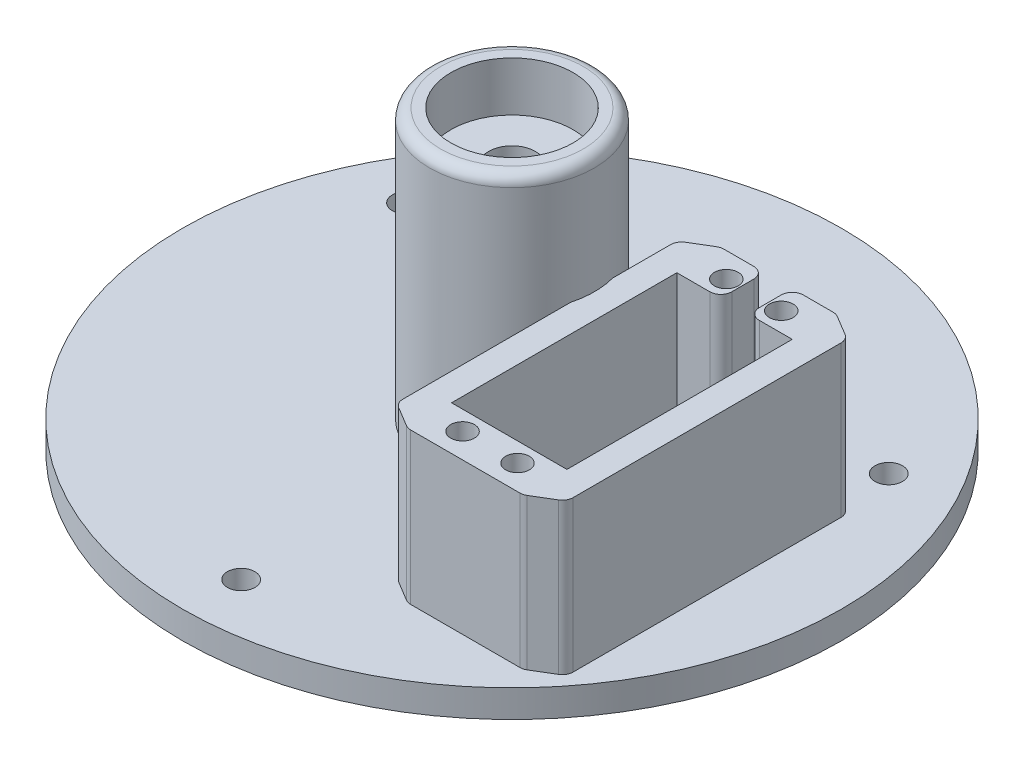
SolidWorks part; units mm, degrees
ref_plane "Front Plane" through (0, 0, 0) normal (0, 0, 1) x (1, 0, 0)
ref_plane "Top Plane" through (0, 0, 0) normal (0, 1, 0) x (1, 0, 0)
ref_plane "Right Plane" through (0, 0, 0) normal (1, 0, 0) x (0, 0, -1)
sketch "Sketch1" plane through (0, 0, 0) normal (0, 1, 0) x (1, 0, 0)
  circle A0 centre (0, 0) radius 60
  circle A1 centre (0, 0) radius 4.25
  dimension "D1" = 120
  dimension "D2" = 8.5
extrude "Boss-Extrude1" add sketch "Sketch1" along normal blind 5
sketch "Sketch2" plane through (0, 5, 0) normal (0, 1, 0) x (1, 0, 0)
  line L0 (20, 10) -> (30, 10) construction
  line L1 (40, 10) -> (40, -30) construction
  line L2 (40, -30) -> (20, -30) construction
  line L3 (20, -30) -> (20, 10) construction
  line L4 (30, 10) -> (30, 0) construction
  line L5 (19.5, 10.5) -> (27.5, 10.5)
  line L6 (40.5, 10.5) -> (40.5, -30.5)
  line L7 (40.5, -30.5) -> (19.5, -30.5)
  line L8 (19.5, -30.5) -> (19.5, 10.5)
  line L10 (45.5, 15.5) -> (45.5, -35.5)
  line L12 (14.5, -35.5) -> (14.5, 15.5)
  line L14 (19.5, 18.5) -> (27.5, 18.5)
  line L17 (19.5, -38.5) -> (40.5, -38.5)
  line L20 (14.5, 15.5) -> (45.5, 15.5) construction
  line L22 (45.5, -35.5) -> (14.5, -35.5) construction
  line L23 (27.5, 10.5) -> (27.5, 18.5)
  line L24 (32.5, 10.5) -> (32.5, 18.5)
  line L25 (32.5, 18.5) -> (40.5, 18.5)
  line L26 (32.5, 10.5) -> (40.5, 10.5)
  line L27 (19.5, 10.5) -> (40.5, 10.5) construction
  line L28 (20, 10) -> (40, 10) construction
  line L29 (14.5, 15.5) -> (19.5, 18.5)
  line L30 (40.5, 18.5) -> (45.5, 15.5)
  line L31 (45.5, -35.5) -> (40.5, -38.5)
  line L32 (19.5, -38.5) -> (14.5, -35.5)
  dimension "D1" = 20
  dimension "D2" = 40
  dimension "D3" = 10
  dimension "D4" = 30
  dimension "D7" = 8
  dimension "D8" = 8
  dimension "D9" = 2.5
  dimension "D5" = 0.5
  dimension "D6" = 5
extrude "Servo housing" add sketch "Sketch2" along normal blind 27.5
sketch "Bearing cut" plane through (0, 0, 0) normal (0, -1, 0) x (1, 0, 0)
  circle A0 centre (0, 0) radius 11.11
  dimension "D1" = 22.22
sketch "Sketch4" plane through (0, 32.5, 0) normal (0, 1, 0) x (1, 0, 0)
  line L0 (30, -30.5) -> (30, 2.8201) construction
  line L1 (40.5, -30.5) -> (19.5, -30.5) construction
  line L2 (19.5, 10.5) -> (27.5, 10.5) construction
  circle A0 centre (25, -34) radius 2.155
  circle A1 centre (25, 14) radius 2.155
  circle A2 centre (35, -34) radius 2.155
  circle A3 centre (35, 14) radius 2.155
  dimension "D2" = 4.31
  dimension "D1" = 5
  dimension "D3" = 48
  dimension "D4" = 3.5
extrude "Cut-Extrude1" cut sketch "Sketch4" against normal blind 6
sketch "Sketch5" plane through (0, 5, 0) normal (0, 1, 0) x (1, 0, 0)
  circle A0 centre (0, 0) radius 15
  circle A1 centre (0, 0) radius 4.25
  dimension "D1" = 8.5
  dimension "D2" = 30
extrude "Boss-Extrude2" add sketch "Sketch5" along normal blind 49
extrude "Cut-Extrude2" cut sketch "Bearing cut" against normal blind 18
sketch "Sketch6" plane through (0, 54, 0) normal (0, 1, 0) x (1, 0, 0)
  circle A0 centre (0, 0) radius 11.11
  dimension "D1" = 22.22
extrude "Cut-Extrude3" cut sketch "Sketch6" against normal blind 9
sketch "Sketch8" plane through (0, 0, 0) normal (0, -1, 0) x (-1, 0, 0)
  circle A0 centre (0, 0) radius 12.5
  dimension "D1" = 25
extrude "Cut-Extrude4" cut sketch "Sketch8" against normal blind 10
fillet "Fillet1" radius 2 2 edges at (27.5, 18.75, -10.5) (32.5, 18.75, -10.5)
fillet "Fillet2" radius 2 10 edges at (14.5, 18.75, -15.5) (27.5, 18.75, -18.5) (32.5, 18.75, -18.5) (19.5, 18.75, -18.5) (40.5, 18.75, -18.5) (45.5, 18.75, -15.5) (45.5, 18.75, 35.5) (40.5, 18.75, 38.5) (19.5, 18.75, 38.5) (14.5, 18.75, 35.5)
fillet "Fillet5" radius 2 1 edges at (0, 54, 15)
sketch "Sketch9" plane through (0, 0, 0) normal (0, -1, 0) x (1, 0, 0)
  line L0 (0, 0) -> (0.7128, 50) construction
  circle A0 centre (0.7128, 50) radius 2.5
  circle A1 centre (42.9449, -25.6173) radius 2.5
  circle A2 centre (-43.6577, -24.3827) radius 2.5
  circle A3 centre (0, 0) radius 11.11 construction
  point P11 (0, 0)
  dimension "D2" = 5
  dimension "D1" = 50
  dimension "D3" = 3
extrude "Cut-Extrude5" cut sketch "Sketch9" against normal blind 10
